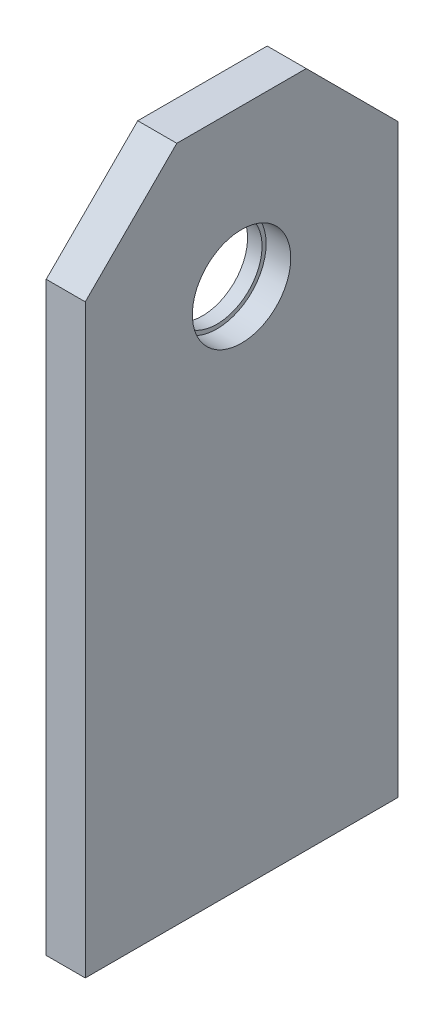
SolidWorks part; units mm, degrees
material "ASTM A36 Steel"
ref_plane "Front Plane" through (0, 0, 0) normal (0, 0, 1) x (1, 0, 0)
ref_plane "Top Plane" through (0, 0, 0) normal (0, 1, 0) x (1, 0, 0)
ref_plane "Right Plane" through (0, 0, 0) normal (1, 0, 0) x (0, 0, -1)
sketch "Sketch1" plane through (0, 0, 0) normal (1, 0, 0) x (0, 0, -1)
  line L0 (-38.1, -127) -> (-38.1, 15.7815)
  line L1 (38.1, 15.7815) -> (38.1, -127)
  line L2 (38.1, -127) -> (-38.1, -127)
  line L3 (47.625, -127) -> (-47.625, -127) construction
  line L4 (-38.1, 15.7815) -> (-15.7815, 38.1)
  line L5 (-15.7815, 38.1) -> (15.7815, 38.1)
  line L6 (15.7815, 38.1) -> (38.1, 15.7815)
  line L7 (0, 38.1) -> (0, 0) construction
  line L8 (0, 0) -> (26.9408, 26.9408) construction
  line L9 (-26.9408, 26.9408) -> (0, 0) construction
  circle A0 centre (0, 0) radius 11
  point P9 (22.8911, 32.3317)
  point P15 (0, 0.985)
  dimension "D1" = 22
  dimension "D2" = 76.2
  dimension "D3" = 45
extrude "Boss-Extrude1" add sketch "Sketch1" along normal mid plane 9.525
sketch "Sketch2" plane through (4.7625, 0, 0) normal (1, 0, 0) x (0, 0, -1)
  circle A0 centre (0, 0) radius 12
  dimension "D1" = 24
extrude "Cut-Extrude1" cut sketch "Sketch2" against normal blind 6
sketch "Sketch3" plane through (0, -127, 0) normal (0, -1, 0) x (1, 0, 0)
  line L0 (0, -30.1625) -> (0, 30.1625) construction
  circle A0 centre (0, 30.1625) radius 2.7781
  circle A1 centre (0, -30.1625) radius 2.7781
  point P4 (0, 0)
  dimension "D1" = 5.5562
  dimension "D2" = 60.325
extrude "Cut-Extrude2" cut sketch "Sketch3" against normal blind 25.4
